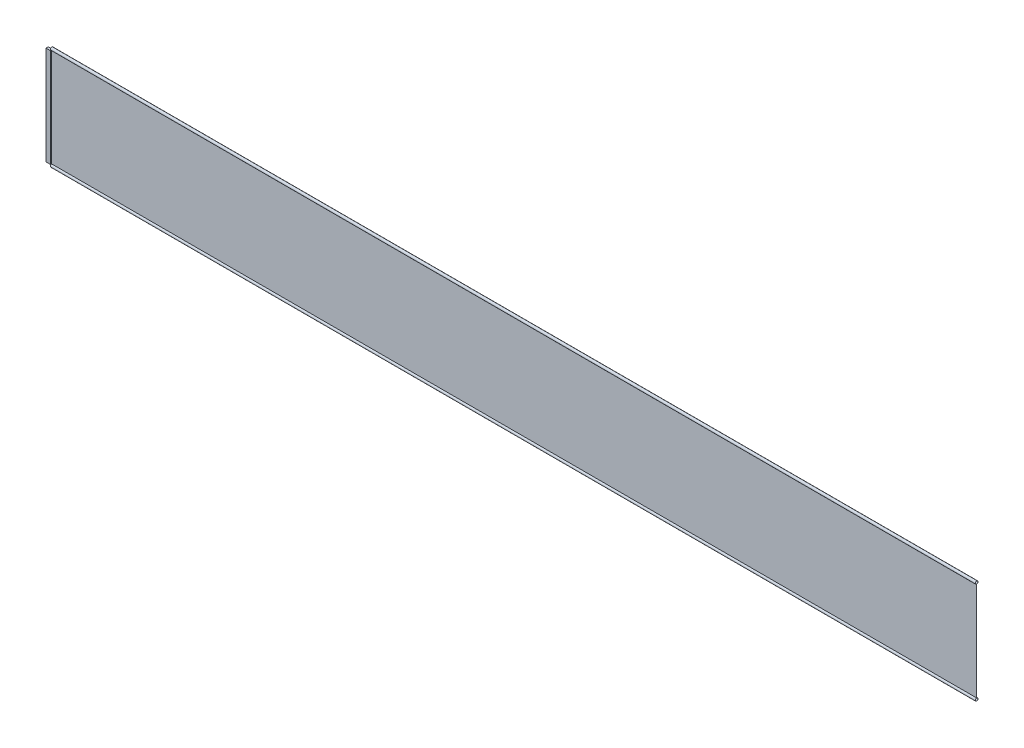
SolidWorks part; units mm, degrees
ref_plane "Front Plane" through (0, 0, 0) normal (0, 0, 1) x (1, 0, 0)
ref_plane "Top Plane" through (0, 0, 0) normal (0, 1, 0) x (1, 0, 0)
ref_plane "Right Plane" through (0, 0, 0) normal (1, 0, 0) x (0, 0, -1)
sketch "Sketch1" plane through (0, 0, 0) normal (0, 0, 1) x (1, 0, 0)
  line L1 (3200, -2150) -> (3400, -2150)
  line L2 (3200, -2150) -> (3200, 2150)
  line L3 (3200, 2150) -> (3400, 2150)
  line L4 (3400, -2150) -> (3400, 2150)
extrude "Boss-Extrude1" add sketch "Sketch1" along normal blind 100 from offset 50
sketch "Sketch2" plane through (0, 0, 0) normal (0, 0, 1) x (1, 0, 0)
  line L1 (3400, -2150) -> (43749.6262, -2150)
  line L2 (3400, -2150) -> (3400, 2150)
  line L3 (3400, 2150) -> (43749.6262, 2150)
  line L4 (43749.6262, -2150) -> (43749.6262, 2150)
extrude "Boss-Extrude2" add sketch "Sketch2" along normal blind 3 from offset 1.5
sketch "Sketch3" plane through (0, 0, 0) normal (1, 0, 0) x (0, 0, -1)
  circle A0 centre (0, -2210) radius 60
  circle A1 centre (0, -2210) radius 57
extrude "Boss-Extrude3" add sketch "Sketch3" along normal blind 40349.6262 from offset 3400
sketch "Sketch4" plane through (0, 0, 0) normal (1, 0, 0) x (0, 0, -1)
  circle A0 centre (0, 2210) radius 60
  circle A1 centre (0, 2210) radius 57
extrude "Boss-Extrude4" add sketch "Sketch4" along normal blind 40349.6262 from offset 3400
